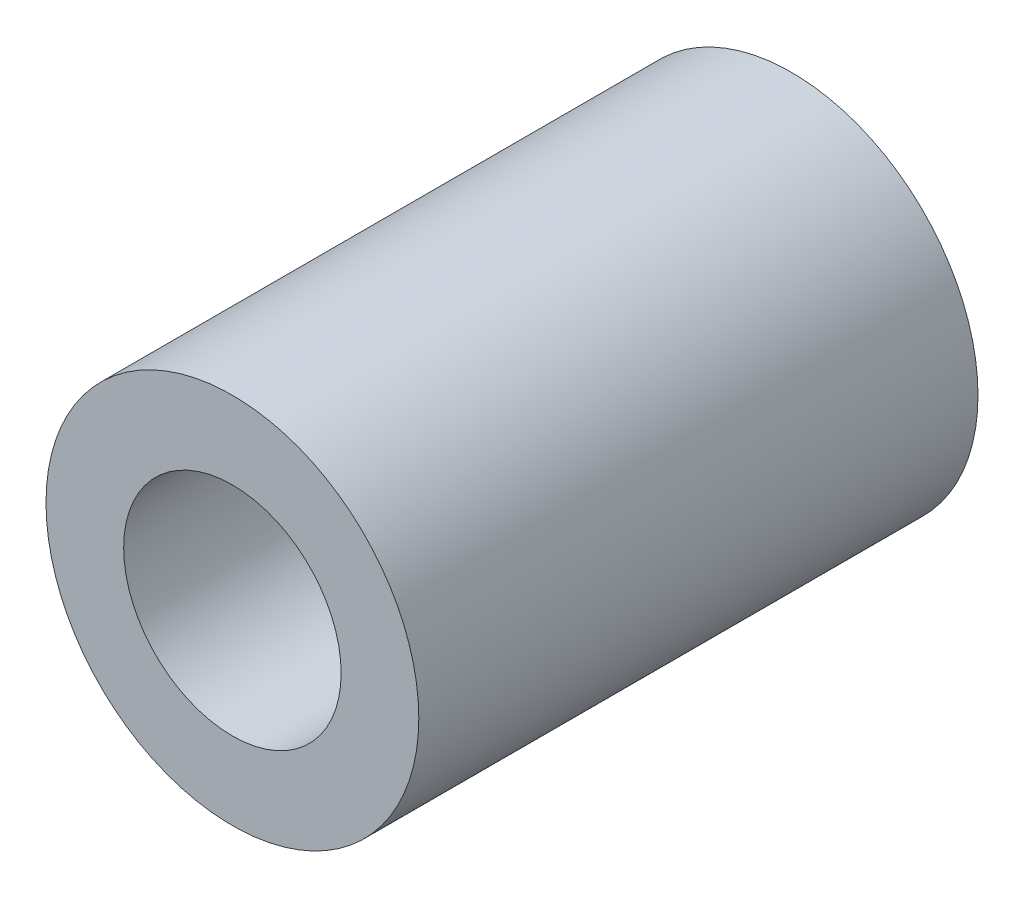
SolidWorks part; units mm, degrees
ref_plane "前视基准面" through (0, 0, 0) normal (0, 0, 1) x (1, 0, 0)
ref_plane "上视基准面" through (0, 0, 0) normal (0, 1, 0) x (1, 0, 0)
ref_plane "右视基准面" through (0, 0, 0) normal (1, 0, 0) x (0, 0, -1)
sketch "草图1" plane through (0, 0, 0) normal (0, 0, 1) x (1, 0, 0)
  circle A0 centre (0, 0) radius 3.5
  circle A1 centre (0, 0) radius 6
extrude "凸台-拉伸1" add sketch "草图1" along normal blind 18
